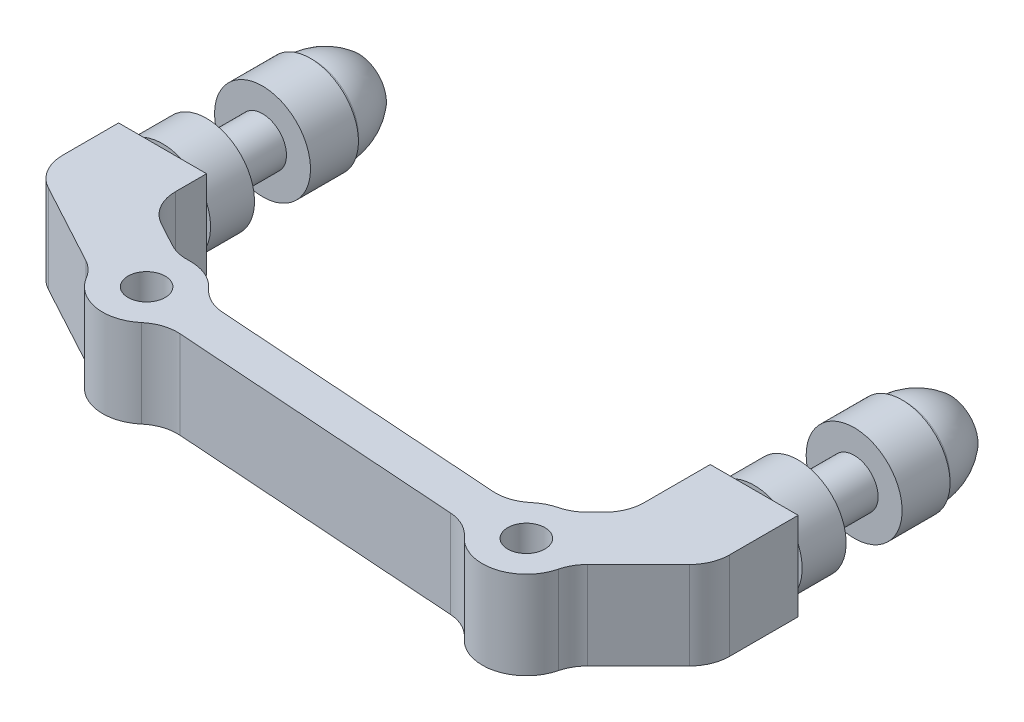
SolidWorks part; units mm, degrees
ref_plane "Front Plane" through (0, 0, 0) normal (0, 0, 1) x (1, 0, 0)
ref_plane "Top Plane" through (0, 0, 0) normal (0, 1, 0) x (1, 0, 0)
ref_plane "Right Plane" through (0, 0, 0) normal (1, 0, 0) x (0, 0, -1)
sketch "Sketch1" plane through (0, 0, 0) normal (0, 1, 0) x (1, 0, 0)
  line L0 (-55, 0) -> (55, 0) construction
  line L2 (0, -55) -> (0, 55) construction
  line L3 (0, 0) -> (11, 0)
  line L4 (74, 0) -> (85, 0)
  line L5 (0, 0) -> (0, -10)
  line L6 (85, 0) -> (85, -10.6569)
  line L7 (19.5, -16) -> (4.4638, -7.8668) construction
  line L8 (19.5, -16) -> (70.5, -19.5) construction
  line L9 (70.5, -19.5) -> (82.1716, -7.8284) construction
  line L10 (24.2163, -18.8295) -> (65.4414, -21.6587)
  line L11 (24.5586, -13.8413) -> (65.7837, -16.6705)
  line L12 (19.6712, -13.5059) -> (70.6712, -17.0059) construction
  line L13 (19.3288, -18.4941) -> (70.3288, -21.9941) construction
  line L14 (18.0828, -10.6857) -> (11, -6.8546)
  line L15 (75.9977, -19.6592) -> (85, -10.6569)
  line L16 (14.2766, -17.7223) -> (0, -10)
  line L17 (70.3408, -14.0023) -> (74, -10.3431)
  line L18 (17.5969, -19.5183) -> (0, -10) construction
  line L19 (21.4031, -12.4817) -> (3.8061, -2.9634) construction
  line L20 (67.6716, -16.6716) -> (79.3431, -5) construction
  line L21 (73.3284, -22.3284) -> (85, -10.6569) construction
  line L22 (19.5, -16) -> (1.9031, -6.4817) construction
  line L23 (11, 0) -> (11, -6.8546)
  line L24 (74, 0) -> (74, -10.3431)
  circle A0 centre (19.5, -16) radius 2.3283
  circle A1 centre (70.5, -19.5) radius 2.3283
  arc A2 (24.5586, -13.8413) -> (18.0828, -10.6857) centre (19.5, -16) ccw
  arc A3 (65.4414, -21.6587) -> (75.9977, -19.6592) centre (70.5, -19.5) ccw
  arc A4 (14.2766, -17.7223) -> (24.2163, -18.8295) centre (19.5, -16) ccw
  arc A5 (70.3408, -14.0023) -> (65.7837, -16.6705) centre (70.5, -19.5) ccw
  dimension "D5" = 11
  dimension "D1" = 16
  dimension "D2" = 19.5
  dimension "D3" = 19.5
  dimension "D4" = 70.5
  dimension "D6" = 85
  dimension "D7" = 10
  dimension "D12" = 45
  dimension "D13" = 11
  dimension "D8" = 2.5
  dimension "D9" = 2.5
  dimension "D10" = 4
  dimension "D11" = 4
extrude "Boss-Extrude1" add sketch "Sketch1" along normal mid plane 11
fillet "Fillet1" radius 5 12 edges at (85, 0, 10.6569) (0, 0, 10) (11, 0, 6.8546) (24.5586, 0, 13.8413) (18.0828, 0, 10.6857) (65.7837, 0, 16.6705) (74, 0, 10.3431) (70.3408, 0, 14.0023) (75.9977, 0, 19.6592) (65.4414, 0, 21.6587) (24.2163, 0, 18.8295) (14.2766, 0, 17.7223)
sketch "Sketch3" plane through (0, 0, 0) normal (0, 0, -1) x (-1, 0, 0)
  line L0 (13.75, 0) -> (-13.75, 0) construction
  line L3 (-85, 5.5) -> (-74, 5.5) construction
  line L4 (-79.5, 5.5) -> (-79.5, -5.5) construction
  line L5 (-85, -5.5) -> (-74, -5.5) construction
  circle A0 centre (-79.5, 0) radius 6
  circle A1 centre (-5.5, 0) radius 6
  dimension "D2" = 12
  dimension "D1" = 74
extrude "Boss-Extrude2" add sketch "Sketch3" along normal blind 5.5
sketch "Sketch4" plane through (0, 0, -5.5) normal (0, 0, -1) x (-1, 0, 0)
  circle A0 centre (-79.5, 0) radius 3
  circle A1 centre (-5.5, 0) radius 3
  dimension "D1" = 6
extrude "Boss-Extrude3" add sketch "Sketch4" along normal blind 7
sketch "Sketch5" plane through (0, 0, 0) normal (0, 1, 0) x (1, 0, 0)
  line L0 (5.5, 12.5) -> (5.5, 0) construction
  line L1 (8.5, 12.5) -> (2.5, 12.5) construction
  line L2 (-6.6, 0) -> (6.6, 0) construction
  line L3 (5.5, 12.5) -> (11.5, 12.5)
  line L4 (11.5, 12.5) -> (11.5, 18.5)
  line L6 (9, 24.5) -> (5.5, 24.5)
  line L7 (5.5, 24.5) -> (5.5, 12.5)
  line L8 (11, 19) -> (11, 18.5)
  line L9 (11, 18.5) -> (11.5, 18.5)
  arc A0 (11, 19) -> (9, 24.5) centre (2.4375, 19) ccw
  dimension "D1" = 12
  dimension "D2" = 6
  dimension "D3" = 0.5
  dimension "D4" = 7
  dimension "D5" = 12
revolve "Revolve1" add sketch "Sketch5" angle 360 about L0
pattern_linear "LPattern1" count 2 spacing 74 along (1, 0, 0) of "Revolve1"
